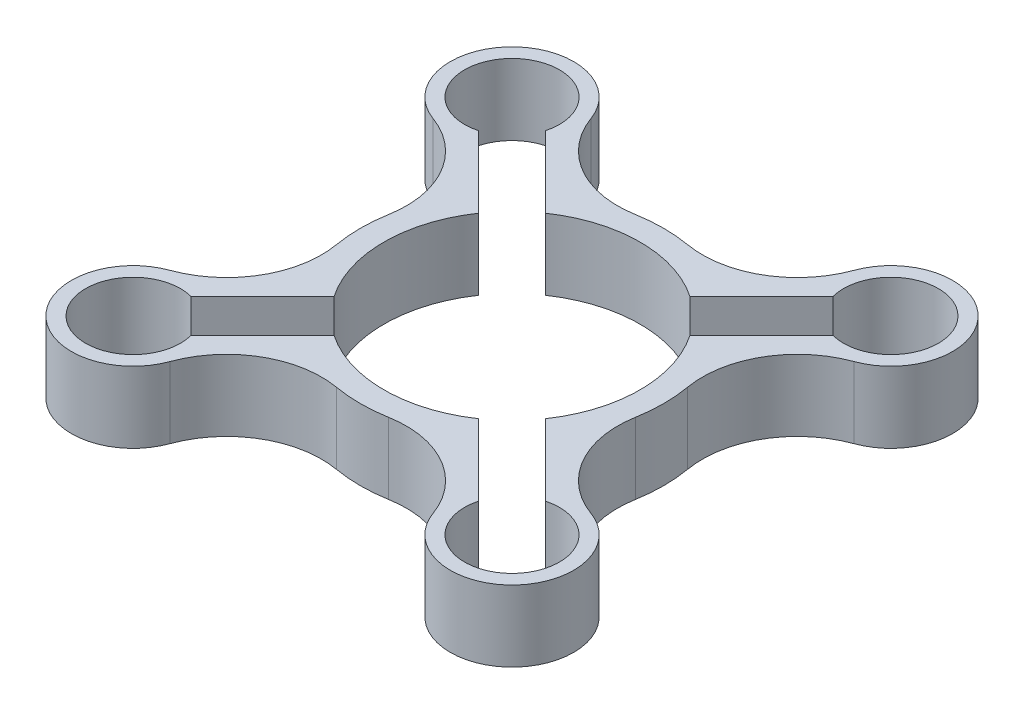
SolidWorks part; units mm, degrees
ref_plane "Front Plane" through (0, 0, 0) normal (0, 0, 1) x (1, 0, 0)
ref_plane "Top Plane" through (0, 0, 0) normal (0, 1, 0) x (1, 0, 0)
ref_plane "Right Plane" through (0, 0, 0) normal (1, 0, 0) x (0, 0, -1)
sketch "Sketch1" plane through (0, 0, 0) normal (0, 1, 0) x (1, 0, 0)
  line L0 (0, 0) -> (77.7369, 0) construction
  line L1 (0, 0) -> (0, 33.3342) construction
  line L2 (0, 0) -> (61.6464, 61.6464) construction
  arc A0 (-31.5238, 5.4999) -> (-31.5238, -5.4999) centre (0, 0) ccw
  arc A1 (44.3931, 27.7338) -> (27.7338, 44.3931) centre (39.9515, 39.9515) ccw
  circle A3 centre (0, 0) radius 56.5 construction
  arc A4 (27.7338, -44.3931) -> (44.3931, -27.7338) centre (39.9515, -39.9515) ccw
  arc A5 (-44.3931, -27.7338) -> (-27.7338, -44.3931) centre (-39.9515, -39.9515) ccw
  arc A6 (-27.7338, 44.3931) -> (-44.3931, 27.7338) centre (-39.9515, 39.9515) ccw
  arc A9 (5.4999, 31.5238) -> (27.7338, 44.3931) centre (8.9373, 51.2262) ccw
  arc A10 (-5.4999, 31.5238) -> (-27.7338, 44.3931) centre (-8.9373, 51.2262) cw
  arc A11 (31.5238, 5.4999) -> (44.3931, 27.7338) centre (51.2262, 8.9373) cw
  arc A12 (31.5238, -5.4999) -> (44.3931, -27.7338) centre (51.2262, -8.9373) ccw
  arc A13 (5.4999, -31.5238) -> (27.7338, -44.3931) centre (8.9373, -51.2262) cw
  arc A14 (-5.4999, -31.5238) -> (-27.7338, -44.3931) centre (-8.9373, -51.2262) ccw
  arc A15 (-31.5238, -5.4999) -> (-44.3931, -27.7338) centre (-51.2262, -8.9373) cw
  arc A16 (-31.5238, 5.4999) -> (-44.3931, 27.7338) centre (-51.2262, 8.9373) ccw
  circle A17 centre (0, 0) radius 27
  arc A18 (5.4999, 31.5238) -> (-5.4999, 31.5238) centre (0, 0) ccw
  arc A19 (31.5238, -5.4999) -> (31.5238, 5.4999) centre (0, 0) ccw
  arc A20 (-5.4999, -31.5238) -> (5.4999, -31.5238) centre (0, 0) ccw
  point P1 (-77.2853, -13.8276)
  point P2 (-121.4372, 24.8381)
  point P14 (0, 0)
  point P19 (0, 0)
  point P44 (0, 0)
  dimension "D1" = 113
  dimension "D2" = 64
  dimension "D4" = 26
  dimension "D6" = 20
  dimension "D7" = 4
  dimension "D8" = 54
  dimension "D3" = 45
  dimension "D5" = 4
extrude "Boss-Extrude1" add sketch "Sketch1" along normal blind 15
sketch "Sketch2" plane through (0, 15, 0) normal (0, 1, 0) x (1, 0, 0)
  line L0 (0, 0) -> (39.9515, 39.9515) construction
  line L1 (15.2261, 22.2972) -> (30.2923, 37.3633)
  line L2 (22.2972, 15.2261) -> (37.3633, 30.2923)
  line L3 (22.2972, -15.2261) -> (37.3633, -30.2923)
  line L4 (15.2261, -22.2972) -> (30.2923, -37.3633)
  line L5 (-15.2261, -22.2972) -> (-30.2923, -37.3633)
  line L6 (-22.2972, -15.2261) -> (-37.3633, -30.2923)
  line L7 (-22.2972, 15.2261) -> (-37.3633, 30.2923)
  line L8 (-15.2261, 22.2972) -> (-30.2923, 37.3633)
  arc A0 (37.3633, 30.2923) -> (30.2923, 37.3633) centre (39.9515, 39.9515) ccw
  arc A1 (30.2923, -37.3633) -> (37.3633, -30.2923) centre (39.9515, -39.9515) ccw
  arc A2 (-37.3633, -30.2923) -> (-30.2923, -37.3633) centre (-39.9515, -39.9515) ccw
  arc A3 (-30.2923, 37.3633) -> (-37.3633, 30.2923) centre (-39.9515, 39.9515) ccw
  circle A4 centre (0, 0) radius 27 construction
  arc A5 (15.2261, 22.2972) -> (-15.2261, 22.2972) centre (0, 0) ccw
  arc A6 (-15.2261, -22.2972) -> (15.2261, -22.2972) centre (0, 0) ccw
  arc A7 (22.2972, -15.2261) -> (22.2972, 15.2261) centre (0, 0) ccw
  arc A8 (-22.2972, 15.2261) -> (-22.2972, -15.2261) centre (0, 0) ccw
  point P33 (0, 0)
  dimension "D1" = 20
  dimension "D2" = 10
  dimension "D3" = 4
extrude "Cut-Extrude1" cut sketch "Sketch2" against normal blind 15
